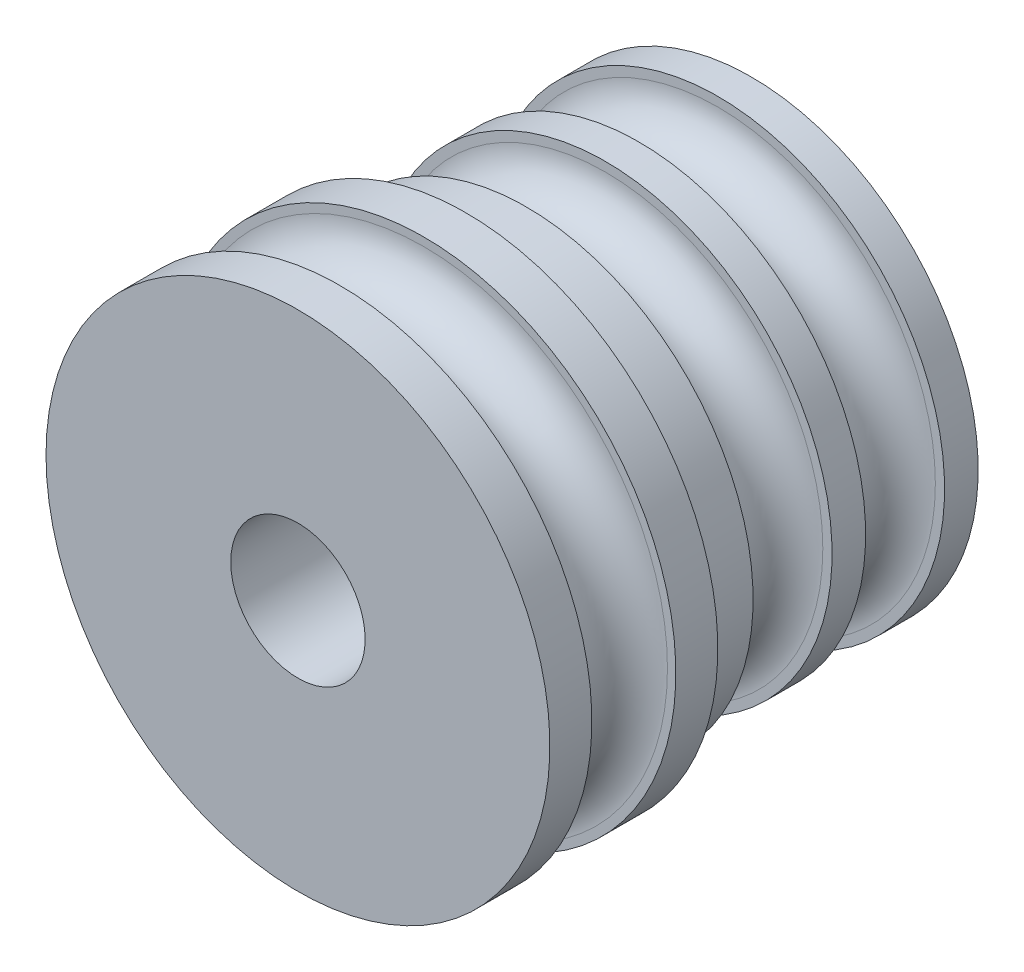
SolidWorks part; units mm, degrees
ref_plane "Front Plane" through (0, 0, 0) normal (0, 0, 1) x (1, 0, 0)
ref_plane "Top Plane" through (0, 0, 0) normal (0, 1, 0) x (1, 0, 0)
ref_plane "Right Plane" through (0, 0, 0) normal (1, 0, 0) x (0, 0, -1)
sketch "Sketch1" plane through (0, 0, 0) normal (0, 1, 0) x (1, 0, 0)
  line L0 (-56.5563, 59.8877) -> (-56.5563, -10.1123) construction
  line L1 (-52.5563, 30.1097) -> (-52.5563, 3.1097)
  line L2 (-52.5563, 3.1097) -> (-41.5563, 3.1097)
  line L3 (-41.5563, 3.1097) -> (-41.5563, 5.6097)
  line L4 (-41.5563, 13.1097) -> (-43.0563, 13.1097)
  line L5 (-43.0563, 13.1097) -> (-43.0563, 16.7097)
  line L6 (-43.0563, 30.1097) -> (-52.5563, 30.1097)
  line L8 (-42.0563, 5.6097) -> (-41.5563, 5.6097)
  line L9 (-43.6063, 28.1097) -> (-43.0563, 28.1097)
  line L10 (-42.0563, 10.6097) -> (-41.5563, 10.6097)
  line L11 (-43.6063, 23.4097) -> (-43.0563, 23.4097)
  line L12 (-43.0563, 28.1097) -> (-43.0563, 30.1097)
  line L13 (-43.6063, 21.4097) -> (-43.0563, 21.4097)
  line L14 (-43.0563, 21.4097) -> (-43.0563, 23.4097)
  line L15 (-43.6063, 16.7097) -> (-43.0563, 16.7097)
  line L16 (-41.5563, 10.6097) -> (-41.5563, 13.1097)
  arc A0 (-42.0563, 10.6097) -> (-42.0563, 5.6097) centre (-42.0563, 8.1097) ccw
  arc A1 (-43.6063, 28.1097) -> (-43.6063, 23.4097) centre (-43.6063, 25.7597) ccw
  arc A2 (-43.6063, 21.4097) -> (-43.6063, 16.7097) centre (-43.6063, 19.0597) ccw
  dimension "D1" = 27
  dimension "D10" = 4.7
  dimension "D11" = 2
  dimension "D12" = 6.7
  dimension "D4" = 10
  dimension "D8" = 5
  dimension "D5" = 5
  dimension "D9" = 4.7
  dimension "D13" = 12.95
  dimension "D2" = 70
  dimension "D3" = 4
  dimension "D6" = 15
  dimension "D7" = 14.5
  dimension "D14" = 13.5
revolve "Revolve1" add sketch "Sketch1" angle 360 about L0
